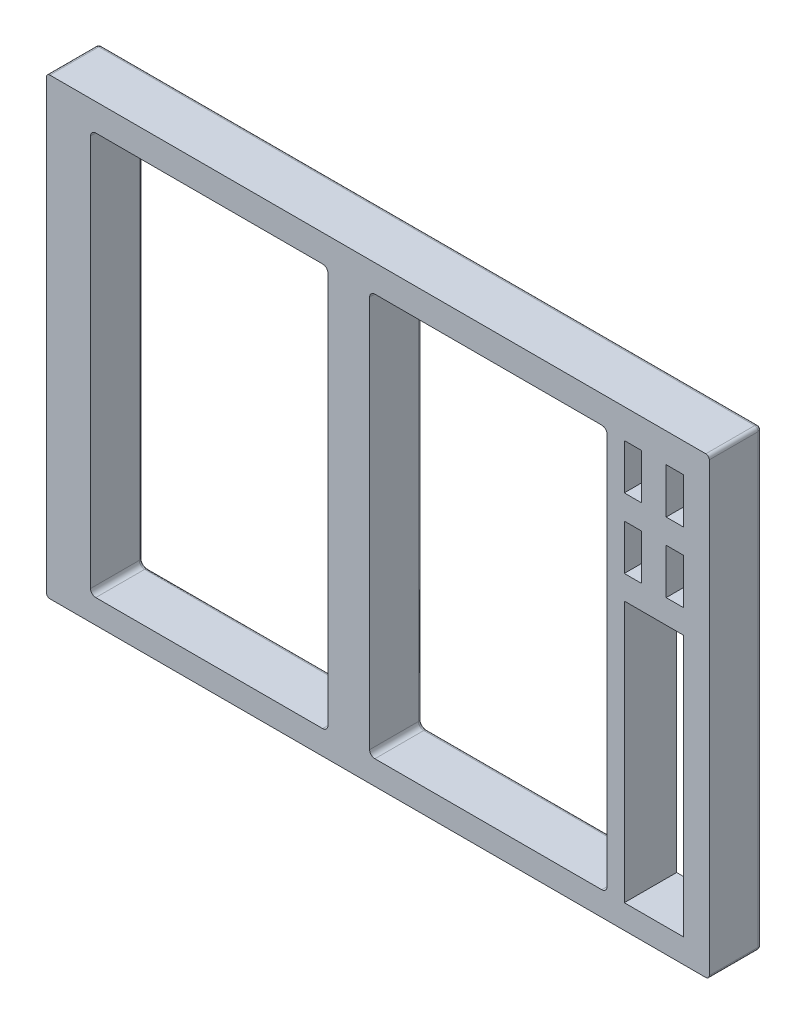
SolidWorks part; units mm, degrees
material "Mousse de polyuréthane flexible"
ref_plane "Plan de face" through (0, 0, 0) normal (0, 0, 1) x (1, 0, 0)
ref_plane "Plan de dessus" through (0, 0, 0) normal (0, 1, 0) x (1, 0, 0)
ref_plane "Plan de droite" through (0, 0, 0) normal (1, 0, 0) x (0, 0, -1)
sketch "Esquisse2" plane through (0, 0, 0) normal (0, 0, 1) x (1, 0, 0)
  line L0 (150.4918, -120.1916) -> (148.59, -120.1916) construction
  line L1 (149.84, -48.26) -> (213.38, -48.26)
  line L3 (149.59, -163.576) -> (213.63, -163.576)
  line L5 (213.329, -157.77) -> (214.63, -157.77) construction
  line L6 (229.84, -48.26) -> (293.38, -48.26)
  line L7 (211.729, -159.87) -> (211.729, -163.576) construction
  line L8 (229.59, -163.576) -> (293.63, -163.576)
  line L9 (211.729, -161.723) -> (213.9795, -161.723) construction
  line L10 (152.166, -118.078) -> (152.166, -115.9321) construction
  line L11 (294.1269, -163.6747) -> (229.0926, -163.6747)
  line L12 (171.45, -157.48) -> (174.45, -157.48) construction
  line L28 (168.45, -160.226) -> (174.45, -154.734) construction
  line L29 (168.45, -154.734) -> (174.45, -160.226) construction
  line L39 (148.632, -115.1937) -> (154.136, -110.3583) construction
  line L40 (148.632, -110.3583) -> (154.136, -115.1937) construction
  line L46 (215.8814, -117.435) -> (208.8197, -113.4466) construction
  line L47 (215.8814, -112.435) -> (207.0286, -117.435) construction
  line L48 (148.59, -49.51) -> (147.5926, -49.51) construction
  line L53 (147.5926, -49.51) -> (147.5926, -48.3587) construction
  line L54 (214.63, -162.576) -> (215.6269, -162.576) construction
  line L55 (215.6269, -162.576) -> (215.6269, -163.6747) construction
  line L56 (198.12, -157.48) -> (201.1151, -157.48) construction
  line L57 (214.1269, -163.6747) -> (149.0926, -163.6747)
  line L58 (215.6269, -162.1747) -> (215.6269, -49.8587)
  line L59 (214.1269, -48.3587) -> (149.0926, -48.3587)
  line L60 (147.5926, -162.1747) -> (147.5926, -49.8587)
  line L66 (195.1249, -160.226) -> (201.1151, -154.734) construction
  line L67 (195.1249, -154.734) -> (201.1151, -160.226) construction
  line L68 (295.6269, -162.1747) -> (295.6269, -49.8587)
  line L69 (294.1269, -48.3587) -> (229.0926, -48.3587)
  line L70 (227.5926, -162.1747) -> (227.5926, -49.8587)
  line L71 (230.4918, -120.1916) -> (228.59, -120.1916) construction
  line L72 (293.329, -157.77) -> (294.63, -157.77) construction
  line L73 (291.729, -159.87) -> (291.729, -163.576) construction
  line L74 (291.729, -161.723) -> (293.9795, -161.723) construction
  line L75 (232.166, -118.078) -> (232.166, -115.9321) construction
  line L76 (251.45, -157.48) -> (254.45, -157.48) construction
  line L77 (248.45, -160.226) -> (254.45, -154.734) construction
  line L78 (248.45, -154.734) -> (254.45, -160.226) construction
  line L79 (228.632, -115.1937) -> (234.136, -110.3583) construction
  line L80 (228.632, -110.3583) -> (234.136, -115.1937) construction
  line L81 (295.8814, -117.435) -> (288.8197, -113.4466) construction
  line L82 (295.8814, -112.435) -> (287.0286, -117.435) construction
  line L83 (228.59, -49.51) -> (227.5926, -49.51) construction
  line L84 (227.5926, -49.51) -> (227.5926, -48.3587) construction
  line L85 (294.63, -162.576) -> (295.6269, -162.576) construction
  line L86 (295.6269, -162.576) -> (295.6269, -163.6747) construction
  line L87 (278.12, -157.48) -> (281.1151, -157.48) construction
  line L88 (275.1249, -160.226) -> (281.1151, -154.734) construction
  line L89 (275.1249, -154.734) -> (281.1151, -160.226) construction
  line L90 (148.032, -48.7981) -> (311.864, -162.3156) construction
  line L91 (-2.5, 6.5) -> (2.5, 6.5)
  line L92 (134.948, -170.5568) -> (324.948, -170.5568)
  line L93 (134.948, -170.5568) -> (134.948, -40.5568)
  line L94 (134.948, -40.5568) -> (324.948, -40.5568)
  line L95 (324.948, -170.5568) -> (324.948, -40.5568)
  line L96 (134.948, -170.5568) -> (324.948, -40.5568) construction
  line L97 (134.948, -40.5568) -> (324.948, -170.5568) construction
  line L98 (-2.5, 6.5) -> (-2.5, -6.5)
  line L99 (-2.5, -6.5) -> (2.5, -6.5)
  line L100 (2.5, 6.5) -> (2.5, -6.5)
  line L101 (312.5799, -48.9432) -> (317.5799, -48.9432)
  line L102 (300.5799, -61.9432) -> (305.5799, -61.9432)
  line L103 (300.5799, -61.9432) -> (300.5799, -48.9432)
  line L104 (300.5799, -48.9432) -> (305.5799, -48.9432)
  line L105 (305.5799, -61.9432) -> (305.5799, -48.9432)
  line L106 (317.5799, -61.9432) -> (317.5799, -48.9432)
  line L107 (312.5799, -61.9432) -> (317.5799, -61.9432)
  line L108 (312.5799, -61.9432) -> (312.5799, -48.9432)
  line L109 (312.5799, -68.9432) -> (317.5799, -68.9432)
  line L110 (317.5799, -81.9432) -> (317.5799, -68.9432)
  line L111 (312.5799, -81.9432) -> (317.5799, -81.9432)
  line L112 (312.5799, -81.9432) -> (312.5799, -68.9432)
  line L113 (300.5799, -68.9432) -> (305.5799, -68.9432)
  line L114 (305.5799, -81.9432) -> (305.5799, -68.9432)
  line L115 (300.5799, -81.9432) -> (305.5799, -81.9432)
  line L116 (300.5799, -81.9432) -> (300.5799, -68.9432)
  line L118 (300.5799, -88.7888) -> (317.5799, -88.7888)
  line L119 (300.5799, -88.7888) -> (300.5799, -163.6747)
  line L120 (300.5799, -163.6747) -> (317.5799, -163.6747)
  line L121 (317.5799, -88.7888) -> (317.5799, -163.6747)
  arc A14 (215.6269, -162.1747) -> (214.1269, -163.6747) centre (214.1269, -162.1747) cw
  arc A15 (215.6269, -49.8587) -> (214.1269, -48.3587) centre (214.1269, -49.8587) ccw
  arc A16 (147.5926, -49.8587) -> (149.0926, -48.3587) centre (149.0926, -49.8587) cw
  arc A17 (149.0926, -163.6747) -> (147.5926, -162.1747) centre (149.0926, -162.1747) cw
  arc A18 (295.6269, -162.1747) -> (294.1269, -163.6747) centre (294.1269, -162.1747) cw
  arc A19 (295.6269, -49.8587) -> (294.1269, -48.3587) centre (294.1269, -49.8587) ccw
  arc A20 (227.5926, -49.8587) -> (229.0926, -48.3587) centre (229.0926, -49.8587) cw
  arc A21 (229.0926, -163.6747) -> (227.5926, -162.1747) centre (229.0926, -162.1747) cw
  point P101 (254.45, -161.723)
  point P107 (281.1151, -161.723)
  point P108 (229.948, -105.5568)
  point P127 (174.45, -161.723)
  point P130 (201.1151, -161.723)
  dimension "D1" = 1.5
  dimension "D2" = 2
  dimension "D4" = 130
  dimension "D5" = 190
  dimension "D7" = 5
  dimension "D8" = 13
  dimension "D9" = 2
  dimension "D3" = 3
  dimension "D6" = 5
  dimension "D10" = 2
extrude "Boss.-Extru.1" add sketch "Esquisse2" along normal blind 15
fillet "Congé1" radius 1 32 edges at (312.5799, -75.4432, 0) (315.0799, -68.9432, 0) (317.5799, -75.4432, 0) (315.0799, -81.9432, 0) (300.5799, -75.4432, 0) (303.0799, -68.9432, 0) (305.5799, -75.4432, 0) (303.0799, -81.9432, 0) (228.032, -163.2354, 0) (227.5926, -106.0167, 0) (228.032, -48.7981, 0) (261.6098, -48.3587, 0) (295.1876, -48.7981, 0) (295.6269, -106.0167, 0) (295.1876, -163.2354, 0) (261.6098, -163.6747, 0) (148.032, -163.2354, 0) (147.5926, -106.0167, 0) (148.032, -48.7981, 0) (181.6098, -48.3587, 0) (215.1876, -48.7981, 0) (215.6269, -106.0167, 0) (215.1876, -163.2354, 0) (181.6098, -163.6747, 0) (324.948, -105.5568, 0) (229.948, -40.5568, 0) (134.948, -105.5568, 0) (229.948, -170.5568, 0) (134.948, -40.5568, 7.5) (134.948, -170.5568, 7.5) (324.948, -170.5568, 7.5) (324.948, -40.5568, 7.5)
